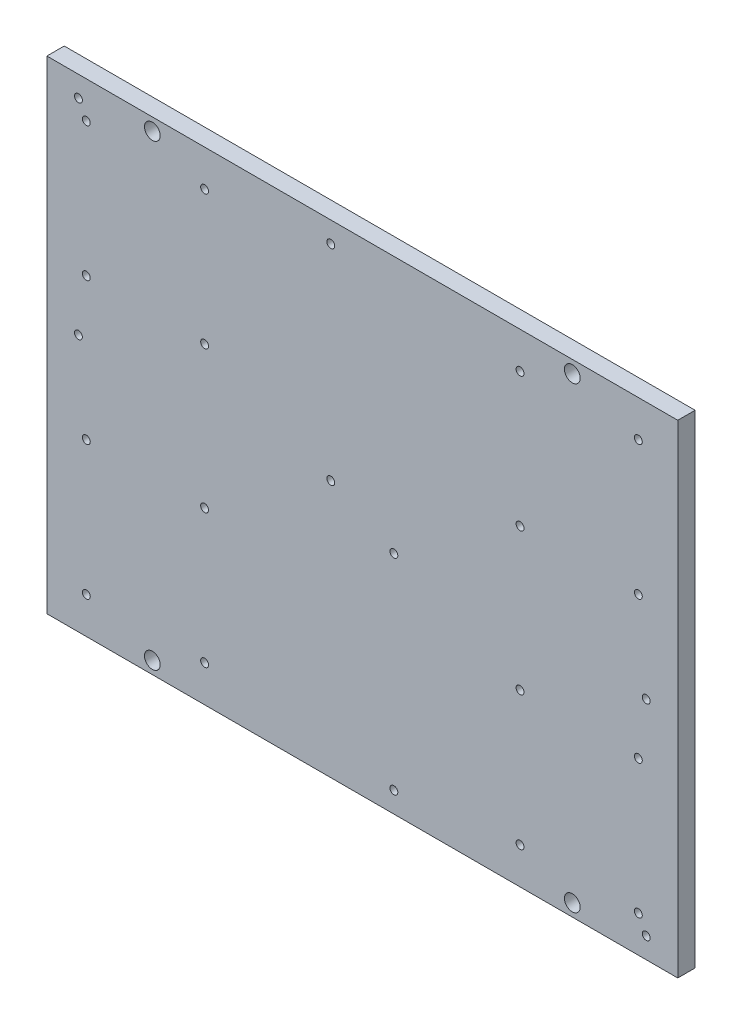
SolidWorks part; units mm, degrees
material "ABS PC"
ref_plane "Front Plane" through (0, 0, 0) normal (0, 0, 1) x (1, 0, 0)
ref_plane "Top Plane" through (0, 0, 0) normal (0, 1, 0) x (1, 0, 0)
ref_plane "Right Plane" through (0, 0, 0) normal (1, 0, 0) x (0, 0, -1)
sketch "Sketch1" plane through (0, 0, 0) normal (0, 0, 1) x (1, 0, 0)
  line L1 (-101.6, -77.7875) -> (101.6, -77.7875)
  line L2 (-101.6, -77.7875) -> (-101.6, 77.7875)
  line L3 (-101.6, 77.7875) -> (101.6, 77.7875)
  line L4 (101.6, -77.7875) -> (101.6, 77.7875)
  line L5 (-101.6, -77.7875) -> (101.6, 77.7875) construction
  line L6 (-101.6, 77.7875) -> (101.6, -77.7875) construction
  point P0 (0, 0)
  dimension "D1" = 203.2
  dimension "D2" = 155.575
extrude "Boss-Extrude1" add sketch "Sketch1" along normal blind 5.588
sketch "Sketch2" plane through (0, 0, 5.588) normal (0, 0, 1) x (1, 0, 0)
  line L0 (-96.4522, 0) -> (112.0869, 0) construction
  line L1 (0, 89.8994) -> (0, -96.1073) construction
  circle A0 centre (-67.6275, 73.787) radius 2.54
  circle A1 centre (67.6275, 73.787) radius 2.54
  circle A2 centre (67.6275, -73.787) radius 2.54
  circle A3 centre (-67.6275, -73.787) radius 2.54
  dimension "D3" = 5.08
  dimension "D1" = 67.6275
  dimension "D2" = 73.787
extrude "Cut-Extrude1" cut sketch "Sketch2" against normal through all
sketch "Sketch3" plane through (0, 0, 5.588) normal (0, 0, 1) x (1, 0, 0)
  line L0 (-96.2223, 0) -> (108.638, 0) construction
  line L1 (-91.44, 5.08) -> (-10.16, 5.08) construction
  line L2 (-91.44, 5.08) -> (-91.44, 71.12) construction
  line L3 (-91.44, 71.12) -> (-10.16, 71.12) construction
  line L4 (-10.16, 5.08) -> (-10.16, 71.12) construction
  line L5 (-91.44, 5.08) -> (-10.16, 71.12) construction
  line L6 (-91.44, 71.12) -> (-10.16, 5.08) construction
  line L7 (10.16, -71.12) -> (91.44, -5.08) construction
  line L8 (91.44, -71.12) -> (91.44, -5.08) construction
  line L9 (10.16, -5.08) -> (91.44, -5.08) construction
  line L10 (10.16, -71.12) -> (10.16, -5.08) construction
  line L11 (10.16, -71.12) -> (91.44, -71.12) construction
  line L12 (10.16, -5.08) -> (91.44, -71.12) construction
  circle A0 centre (-91.44, 71.12) radius 1.27
  circle A1 centre (-10.16, 71.12) radius 1.27
  circle A2 centre (-10.16, 5.08) radius 1.27
  circle A3 centre (-91.44, 5.08) radius 1.27
  circle A4 centre (10.16, -5.08) radius 1.27
  circle A5 centre (91.44, -71.12) radius 1.27
  circle A6 centre (91.44, -5.08) radius 1.27
  circle A7 centre (10.16, -71.12) radius 1.27
  point P0 (-50.8, 38.1)
  point P7 (50.8, -38.1)
  dimension "D4" = 2.54
  dimension "D5" = 50.8
  dimension "D6" = 66.04
  dimension "D7" = 50.8
  dimension "D1" = 81.28
  dimension "D2" = 66.04
  dimension "D3" = 38.1
  dimension "D8" = 38.1
extrude "H-Bridge_Mounts" cut sketch "Sketch3" against normal through all
sketch "Sketch4" plane through (0, 0, 5.588) normal (0, 0, 1) x (1, 0, 0)
  line L0 (0, 83.5955) -> (0, -84.4378) construction
  line L1 (50.8, 22.86) -> (88.9, 22.86) construction
  line L2 (50.8, 22.86) -> (50.8, 66.04) construction
  line L3 (50.8, 66.04) -> (88.9, 66.04) construction
  line L4 (88.9, 22.86) -> (88.9, 66.04) construction
  line L5 (50.8, 22.86) -> (88.9, 66.04) construction
  line L6 (50.8, 66.04) -> (88.9, 22.86) construction
  line L7 (-108.3373, 0) -> (125.3933, 0) construction
  line L8 (-50.8, 66.04) -> (-88.9, 22.86) construction
  line L9 (-50.8, 22.86) -> (-88.9, 66.04) construction
  line L10 (-88.9, 22.86) -> (-88.9, 66.04) construction
  line L11 (-50.8, 66.04) -> (-88.9, 66.04) construction
  line L12 (-50.8, 22.86) -> (-50.8, 66.04) construction
  line L13 (-50.8, 22.86) -> (-88.9, 22.86) construction
  line L14 (-50.8, -22.86) -> (-88.9, -22.86) construction
  line L15 (-50.8, -22.86) -> (-50.8, -66.04) construction
  line L16 (-50.8, -66.04) -> (-88.9, -66.04) construction
  line L17 (-88.9, -22.86) -> (-88.9, -66.04) construction
  line L18 (-50.8, -22.86) -> (-88.9, -66.04) construction
  line L19 (-50.8, -66.04) -> (-88.9, -22.86) construction
  line L20 (50.8, -66.04) -> (88.9, -22.86) construction
  line L21 (50.8, -22.86) -> (88.9, -66.04) construction
  line L22 (88.9, -22.86) -> (88.9, -66.04) construction
  line L23 (50.8, -66.04) -> (88.9, -66.04) construction
  line L24 (50.8, -22.86) -> (50.8, -66.04) construction
  line L25 (50.8, -22.86) -> (88.9, -22.86) construction
  circle A0 centre (50.8, 22.86) radius 1.27
  circle A1 centre (50.8, 66.04) radius 1.27
  circle A2 centre (88.9, 66.04) radius 1.27
  circle A3 centre (-88.9, 22.86) radius 1.27
  circle A4 centre (-88.9, 66.04) radius 1.27
  circle A5 centre (-50.8, 66.04) radius 1.27
  circle A6 centre (-50.8, 22.86) radius 1.27
  circle A7 centre (88.9, -22.86) radius 1.27
  circle A8 centre (-50.8, -22.86) radius 1.27
  circle A9 centre (-50.8, -66.04) radius 1.27
  circle A10 centre (-88.9, -66.04) radius 1.27
  circle A11 centre (-88.9, -22.86) radius 1.27
  circle A12 centre (88.9, 22.86) radius 1.27
  circle A13 centre (88.9, -66.04) radius 1.27
  circle A14 centre (50.8, -66.04) radius 1.27
  circle A15 centre (50.8, -22.86) radius 1.27
  point P0 (69.85, 44.45)
  point P15 (-150.6615, 76.6468)
  point P16 (9.3703, 9.4756)
  point P23 (-69.85, 44.45)
  point P41 (-69.85, -44.45)
  point P42 (69.85, -44.45)
  dimension "D3" = 2.54
  dimension "D4" = 2.54
  dimension "D5" = 2.54
  dimension "D8" = 2.54
  dimension "D1" = 43.18
  dimension "D2" = 38.1
  dimension "D6" = 44.45
  dimension "D7" = 69.85
extrude "Moto_Mounts" cut sketch "Sketch4" against normal through all
